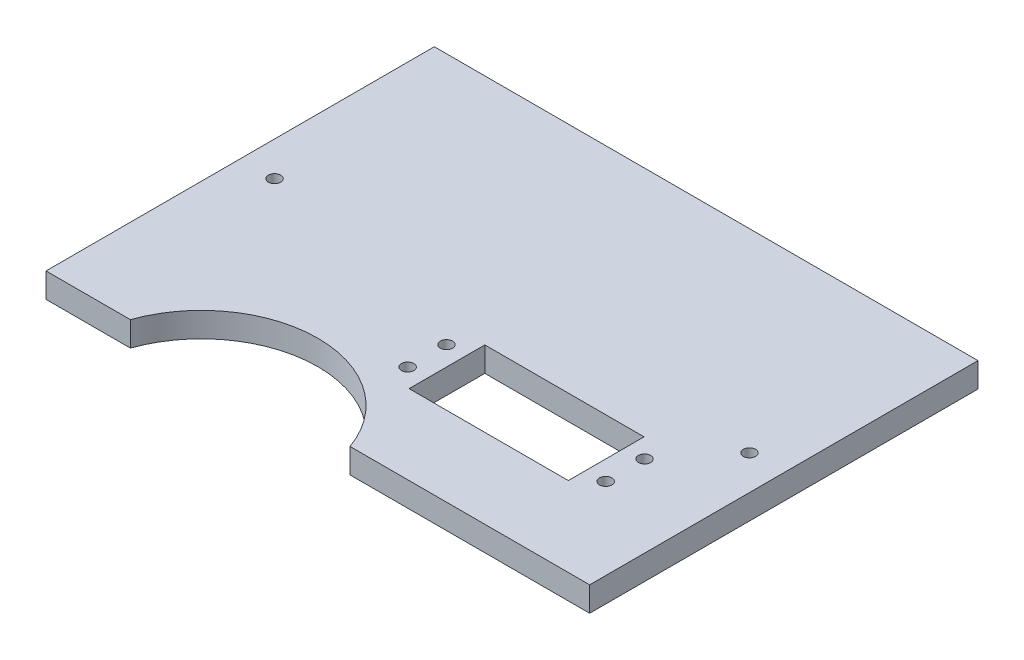
SolidWorks part; units mm, degrees
material "Oak"
ref_plane "Front Plane" through (0, 0, 0) normal (0, 0, 1) x (1, 0, 0)
ref_plane "Top Plane" through (0, 0, 0) normal (0, 1, 0) x (1, 0, 0)
ref_plane "Right Plane" through (0, 0, 0) normal (1, 0, 0) x (0, 0, -1)
sketch "Sketch1" plane through (0, 0, 0) normal (0, 1, 0) x (1, 0, 0)
  line L1 (0, 0) -> (140, 0)
  line L2 (0, 0) -> (0, 100)
  line L3 (0, 100) -> (140, 100)
  line L4 (140, 0) -> (140, 100)
  dimension "D1" = 140
  dimension "D2" = 100
extrude "Boss-Extrude1" add sketch "Sketch1" along normal blind 6.35
sketch "Sketch2" plane through (0, 6.35, 0) normal (0, 1, 0) x (1, 0, 0)
  line L0 (140, 0) -> (140, 100) construction
  line L1 (0, 0) -> (140, 0) construction
  line L3 (73, 40) -> (114, 40)
  line L4 (73, 40) -> (73, 20.5)
  line L5 (73, 20.5) -> (114, 20.5)
  line L6 (114, 40) -> (114, 20.5)
  point P9 (0, 0)
  dimension "D7" = 40
  dimension "D8" = 67
  dimension "D9" = 26
  dimension "D10" = 20.5
extrude "Cut-Extrude1" cut sketch "Sketch2" against normal blind 10
sketch "Sketch3" plane through (0, 6.35, 0) normal (0, 1, 0) x (1, 0, 0)
  line L0 (0, 0) -> (140, 0) construction
  line L1 (0, 100) -> (0, 0) construction
  circle A0 centre (50, -10) radius 30
  dimension "D1" = 60
  dimension "D2" = 10
  dimension "D3" = 50
extrude "Cut-Extrude2" cut sketch "Sketch3" against normal blind 10
sketch "Sketch4" plane through (0, 6.35, 0) normal (0, 1, 0) x (1, 0, 0)
  line L0 (140, 100) -> (0, 100) construction
  line L1 (0, 100) -> (0, 0) construction
  line L2 (140, 0) -> (140, 100) construction
  line L4 (73, 20.5) -> (114, 20.5) construction
  line L7 (114, 20.5) -> (114, 40) construction
  line L8 (73, 40) -> (73, 20.5) construction
  circle A0 centre (131.15, 50) radius 1.5875
  circle A1 centre (8.85, 50) radius 1.5875
  circle A2 centre (68, 25.125) radius 1.5875
  circle A3 centre (119, 35.125) radius 1.5875
  circle A4 centre (68, 35.125) radius 1.5875
  circle A6 centre (119, 25.125) radius 1.5875
  point P24 (62.7, 27.86)
  point P25 (68, 33.16)
  dimension "D1" = 3.175
  dimension "D2" = 3.175
  dimension "D13" = 3.175
  dimension "D14" = 3.175
  dimension "D15" = 3.175
  dimension "D16" = 3.175
  dimension "D3" = 50
  dimension "D4" = 8.85
  dimension "D5" = 8.85
  dimension "D6" = 50
  dimension "D7" = 10
  dimension "D8" = 10
  dimension "D9" = 4.625
  dimension "D10" = 4.625
  dimension "D11" = 5
  dimension "D12" = 5
extrude "Cut-Extrude3" cut sketch "Sketch4" against normal blind 10
